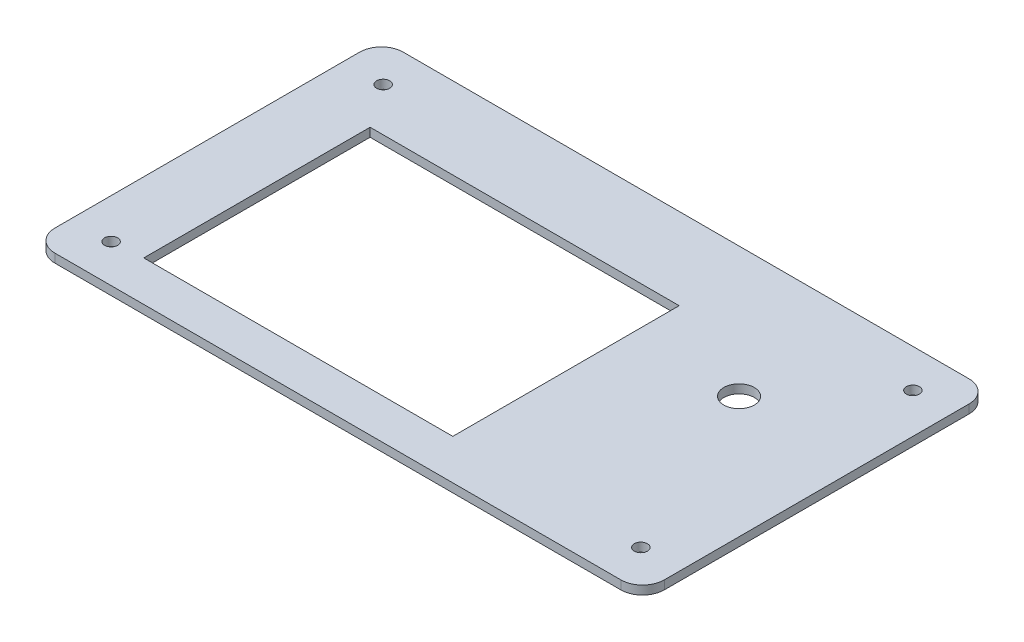
SolidWorks part; units mm, degrees
ref_plane "Front Plane" through (0, 0, 0) normal (0, 0, 1) x (1, 0, 0)
ref_plane "Top Plane" through (0, 0, 0) normal (0, 1, 0) x (1, 0, 0)
ref_plane "Right Plane" through (0, 0, 0) normal (1, 0, 0) x (0, 0, -1)
sketch "Sketch2" plane through (0, 0, 0) normal (0, 1, 0) x (1, 0, 0)
  line L0 (-58.0758, 29.7913) -> (-58.0758, -41.4587) construction
  line L1 (-62.2258, 38.5413) -> (67.7742, 38.5413)
  line L2 (-67.2258, 33.5413) -> (-67.2258, -36.4587)
  line L3 (-62.2258, -41.4587) -> (67.7742, -41.4587)
  line L4 (72.7742, 33.5413) -> (72.7742, -36.4587)
  line L5 (-58.0758, 29.7913) -> (72.7742, 29.7913) construction
  line L6 (-58.0758, -32.7087) -> (72.7742, -32.7087) construction
  line L7 (63.6242, 29.7913) -> (63.6242, -41.4587) construction
  line L8 (19.9242, 8.6487) -> (69.7358, 8.6487) construction
  line L9 (-51.0758, 19.7913) -> (19.9242, 19.7913)
  line L10 (-51.0758, 19.7913) -> (-51.0758, -32.2087)
  line L11 (-51.0758, -32.2087) -> (19.9242, -32.2087)
  line L12 (19.9242, 19.7913) -> (19.9242, -32.2087)
  line L13 (44.83, 8.6487) -> (44.83, -32.7087) construction
  line L14 (44.83, -32.7087) -> (44.83, 29.7913) construction
  circle A0 centre (-58.0758, 29.7913) radius 1.5
  circle A1 centre (63.6242, 29.7913) radius 1.5
  circle A2 centre (-58.0758, -32.7087) radius 1.5
  circle A3 centre (63.6242, -32.7087) radius 1.5
  arc A4 (-62.2258, 38.5413) -> (-67.2258, 33.5413) centre (-62.2258, 33.5413) ccw
  arc A5 (72.7742, 33.5413) -> (67.7742, 38.5413) centre (67.7742, 33.5413) ccw
  arc A6 (67.7742, -41.4587) -> (72.7742, -36.4587) centre (67.7742, -36.4587) ccw
  arc A7 (-62.2258, -41.4587) -> (-67.2258, -36.4587) centre (-62.2258, -36.4587) cw
  circle A8 centre (44.83, 8.6487) radius 3.5
  point P16 (-58.0758, -1.4587)
  point P17 (2.7742, 29.7913)
  point P20 (-67.2258, 38.5413)
  point P23 (72.7742, 38.5413)
  point P28 (-67.2258, -41.4587)
  dimension "D3" = 3
  dimension "D4" = 3
  dimension "D6" = 3
  dimension "D8" = 3
  dimension "D18" = 5
  dimension "D19" = 5
  dimension "D20" = 5
  dimension "D21" = 5
  dimension "D27" = 7
  dimension "D1" = 80
  dimension "D2" = 140
  dimension "D5" = 121.7
  dimension "D7" = 62.5
  dimension "D9" = 62.5
  dimension "D10" = 31.25
  dimension "D12" = 60.85
  dimension "D13" = 70
  dimension "D22" = 52
  dimension "D23" = 71
  dimension "D24" = 7
  dimension "D25" = 10
  dimension "D26" = 0.5
extrude "Boss-Extrude1" add sketch "Sketch2" along normal blind 2
